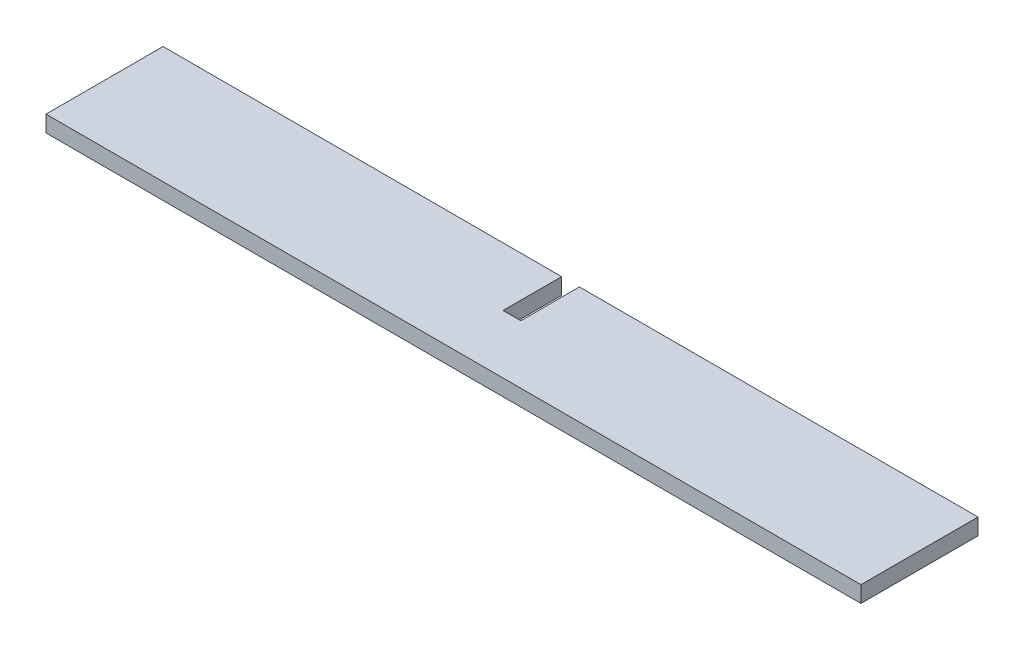
SolidWorks part; units mm, degrees
material "cardboard"
ref_plane "Front Plane" through (0, 0, 0) normal (0, 0, 1) x (1, 0, 0)
ref_plane "Top Plane" through (0, 0, 0) normal (0, 1, 0) x (1, 0, 0)
ref_plane "Right Plane" through (0, 0, 0) normal (1, 0, 0) x (0, 0, -1)
sketch "Sketch1" plane through (0, 0, 0) normal (0, 1, 0) x (1, 0, 0)
  line L0 (-9.8293, 17.4023) -> (43.9707, 17.4023)
  line L1 (-66.0293, 17.4023) -> (-12.2293, 17.4023)
  line L2 (-66.0293, 17.4023) -> (-66.0293, 1.6023)
  line L3 (-66.0293, 1.6023) -> (43.9707, 1.6023)
  line L4 (43.9707, 17.4023) -> (43.9707, 1.6023)
  line L5 (-12.2293, 17.4023) -> (-12.2293, 9.5023)
  line L6 (-9.8293, 17.4023) -> (-9.8293, 9.5023)
  line L7 (-12.2293, 9.5023) -> (-9.8293, 9.5023)
  line L8 (-9.8293, 1.4023) -> (43.9707, 1.4023)
  line L9 (-66.0293, 1.4023) -> (-12.2293, 1.4023)
  line L10 (-66.0293, 1.4023) -> (-66.0293, -14.3977)
  line L11 (-66.0293, -14.3977) -> (43.9707, -14.3977)
  line L12 (43.9707, 1.4023) -> (43.9707, -14.3977)
  line L13 (-12.2293, 1.4023) -> (-12.2293, -6.4977)
  line L14 (-9.8293, 1.4023) -> (-9.8293, -6.4977)
  line L15 (-12.2293, -6.4977) -> (-9.8293, -6.4977)
  line L17 (-66.0293, -14.5977) -> (-12.2293, -14.5977)
  line L18 (49.1565, 9.4023) -> (49.1565, 1.4023)
  line L19 (46.9565, 17.4023) -> (64.9565, 17.4023)
  line L21 (46.9565, 1.4023) -> (49.1565, 1.4023)
  line L23 (51.4565, 9.4023) -> (51.4565, 1.4023)
  line L24 (60.4565, 9.4023) -> (60.4565, 1.4023)
  line L25 (49.1565, 9.4023) -> (51.4565, 9.4023)
  line L26 (60.4565, 9.4023) -> (62.7565, 9.4023)
  line L27 (51.4565, 1.4023) -> (60.4565, 1.4023)
  line L28 (62.7565, 9.4023) -> (62.7565, 1.4023)
  line L29 (62.7565, 1.4023) -> (64.9565, 1.4023)
  line L30 (46.9565, 17.4023) -> (46.9565, 1.4023)
  line L31 (64.9565, 17.4023) -> (64.9565, 1.4023)
  circle A0 centre (55.9565, 9.4023) radius 0.75
extrude "Boss-Extrude1" add sketch "Sketch1" along normal blind 2.2 contours L7 L5 L1 L2 L3 L4 L0 L6
